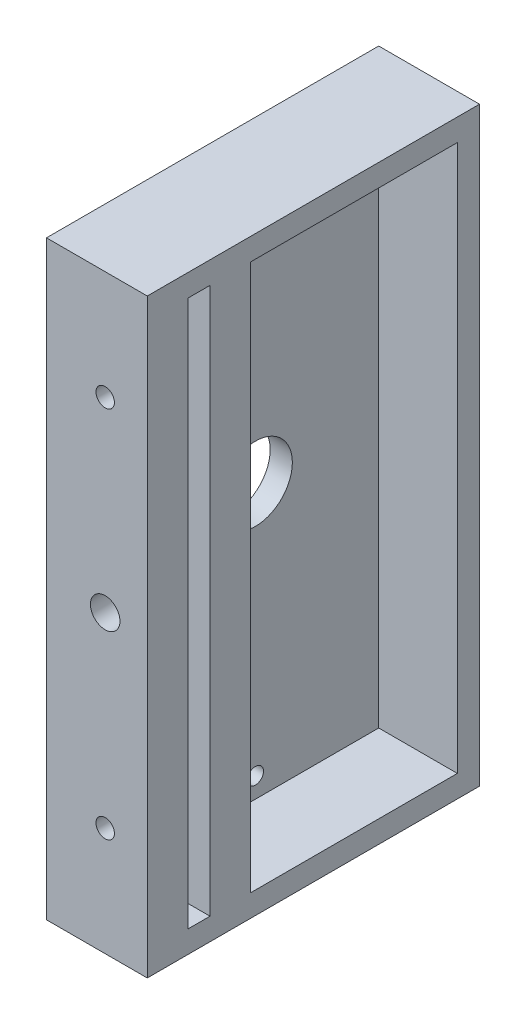
SolidWorks part; units mm, degrees
ref_plane "Front Plane" through (0, 0, 0) normal (0, 0, 1) x (1, 0, 0)
ref_plane "Top Plane" through (0, 0, 0) normal (0, 1, 0) x (1, 0, 0)
ref_plane "Right Plane" through (0, 0, 0) normal (1, 0, 0) x (0, 0, -1)
sketch "Sketch1" plane through (0, 0, 0) normal (0, 1, 0) x (1, 0, 0)
  line L1 (-0.2893, 26.998) -> (2.7107, 26.998)
  line L2 (-0.2893, 26.998) -> (-0.2893, -18.002)
  line L3 (-0.2893, -18.002) -> (2.7107, -18.002)
  line L4 (2.7107, 26.998) -> (2.7107, -18.002)
  line L5 (2.7107, -18.002) -> (13.3604, -18.002)
  line L7 (2.7107, -12.502) -> (13.3604, -12.502)
  line L8 (13.3604, -18.002) -> (13.3604, -12.502)
  line L9 (2.7107, -9.502) -> (13.3604, -9.502)
  line L11 (2.7107, -4.002) -> (13.3604, -4.002)
  line L12 (13.3604, -9.502) -> (13.3604, -4.002)
  dimension "D1" = 3
  dimension "D2" = 3
  dimension "D3" = 5.5
  dimension "D4" = 5.5
  dimension "D5" = 45
extrude "Boss-Extrude1" add sketch "Sketch1" along normal blind 80 contours L9 L12 L11 L4 | L4 L1 L2 L3 | L5 L8 L7 L4
sketch "Sketch2" plane through (0, 0, 4.002) normal (0, 0, -1) x (-1, 0, 0)
  line L0 (-7.6604, 67.0241) -> (-7.6604, 12.9386) construction
  line L3 (-13.3604, 40) -> (-2.7107, 40) construction
  line L4 (-13.3604, 80) -> (-13.3604, 0) construction
  line L5 (-2.7107, 80) -> (-2.7107, 0) construction
  circle A0 centre (-7.6604, 40) radius 2
  circle A1 centre (-7.6604, 65.2738) radius 1.25
  circle A2 centre (-7.6604, 14.7262) radius 1.25
  dimension "D1" = 4
  dimension "D3" = 2.5
  dimension "D2" = 5.7
extrude "Cut-Extrude1" cut sketch "Sketch2" against normal through all
sketch "Sketch3" plane through (2.7107, 0, 0) normal (1, 0, 0) x (0, 0, -1)
  line L0 (26.998, 40) -> (-4.002, 40) construction
  line L1 (26.998, 80) -> (26.998, 0) construction
  line L2 (-4.002, 80) -> (-4.002, 0) construction
  line L3 (-12.502, 80) -> (-12.502, 0) construction
  line L4 (7.298, 78.1833) -> (7.298, 1.9872) construction
  circle A0 centre (7.298, 40) radius 5
  circle A1 centre (7.298, 74.25) radius 1.0922
  circle A2 centre (7.298, 5.75) radius 1.0922
  dimension "D1" = 19.8
  dimension "D2" = 10
  dimension "D3" = 2.1844
  dimension "D4" = 34.25
extrude "Cut-Extrude2" cut sketch "Sketch3" against normal blind 10
sketch "Sketch4" plane through (2.7107, 0, 0) normal (1, 0, 0) x (0, 0, -1)
  line L0 (26.998, 0) -> (-4.002, 0) construction
  line L1 (26.998, 80) -> (23.998, 80)
  line L2 (26.998, 80) -> (26.998, 0)
  line L3 (26.998, 0) -> (23.998, 0)
  line L4 (23.998, 80) -> (23.998, 0)
  line L5 (-12.502, 80) -> (-12.502, 0) construction
  line L6 (23.998, 3) -> (-12.502, 3)
  line L7 (23.998, 3) -> (23.998, 0)
  line L8 (23.998, 0) -> (-12.502, 0)
  line L9 (-12.502, 3) -> (-12.502, 0)
  line L10 (23.998, 80) -> (-12.502, 80)
  line L11 (23.998, 80) -> (23.998, 77)
  line L12 (23.998, 77) -> (-12.502, 77)
  line L13 (-12.502, 80) -> (-12.502, 77)
  line M9 (-4.002, 0) -> (26.998, 0)
  line M10 (26.998, 0) -> (26.998, 80)
  line M11 (26.998, 80) -> (-4.002, 80)
  line M12 (-4.002, 80) -> (-4.002, 0)
  dimension "D1" = 3
  dimension "D2" = 3
  dimension "D3" = 3
extrude "Boss-Extrude2" add sketch "Sketch4" along normal up to surface (10.6497 mm away) contours L4 M11 M9 M10 | L12 L4 M11 M12 | L4 L6 M12 M9 | L10 L13 L12 M12 | L6 L9 L8 M12 up to face at (13.3604, 40, 15.252)
